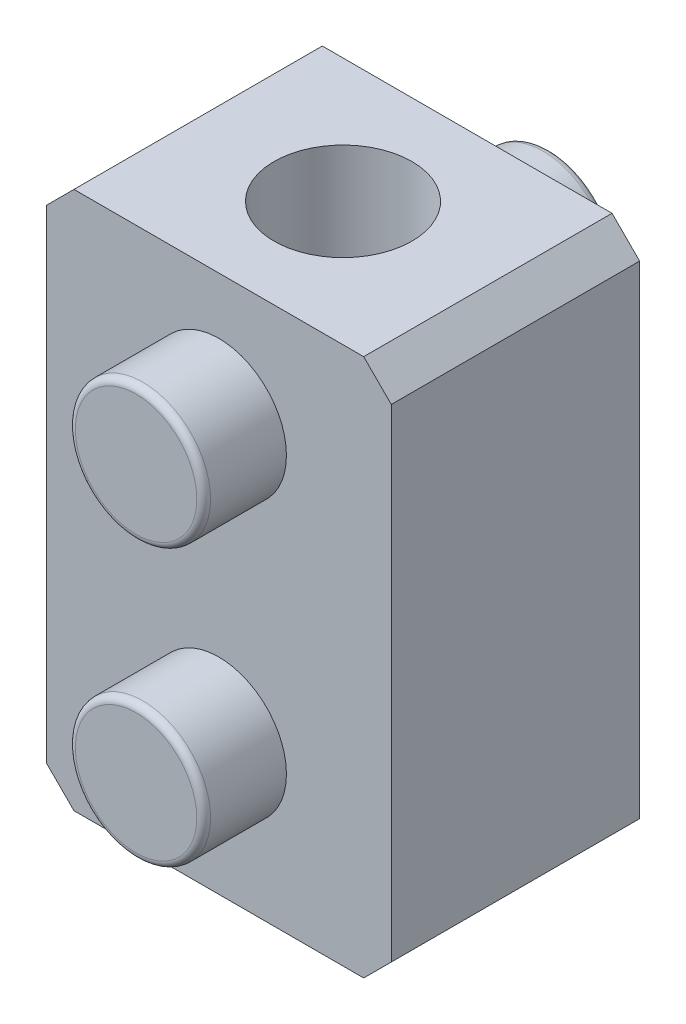
SolidWorks part; units mm, degrees
ref_plane "정면" through (0, 0, 0) normal (0, 0, 1) x (1, 0, 0)
ref_plane "윗면" through (0, 0, 0) normal (0, 1, 0) x (1, 0, 0)
ref_plane "우측면" through (0, 0, 0) normal (1, 0, 0) x (0, 0, -1)
sketch "스케치1" plane through (0, 0, 0) normal (0, 0, 1) x (1, 0, 0)
  line L1 (-6.25, 9.75) -> (6.25, 9.75)
  line L2 (-6.25, 9.75) -> (-6.25, -9.75)
  line L3 (-6.25, -9.75) -> (6.25, -9.75)
  line L4 (6.25, 9.75) -> (6.25, -9.75)
  line L5 (-6.25, 9.75) -> (6.25, -9.75) construction
  line L6 (-6.25, -9.75) -> (6.25, 9.75) construction
  point P0 (0, 0)
  dimension "D1" = 12.5
  dimension "D2" = 19.5
extrude "보스-돌출1" add sketch "스케치1" along normal blind 9
sketch "스케치2" plane through (0, 0, 9) normal (0, 0, 1) x (1, 0, 0)
  line L0 (0, 9.75) -> (0, -9.75) construction
  line L1 (6.25, 9.75) -> (-6.25, 9.75) construction
  line L2 (-6.25, -9.75) -> (6.25, -9.75) construction
  circle A0 centre (0, 5.25) radius 2.45
  circle A1 centre (0, -4.75) radius 2.45
  dimension "D1" = 4.9
  dimension "D2" = 4.9
  dimension "D3" = 10
  dimension "D4" = 5
extrude "보스-돌출2" add sketch "스케치2" along normal blind 3 contours A1 | A0
sketch "스케치4" plane through (0, 0, 0) normal (0, 0, -1) x (-1, 0, 0)
  line L4 (-6.25, 9.75) -> (-6.25, -9.75)
  line L5 (-6.25, -9.75) -> (6.25, -9.75)
  line L6 (6.25, -9.75) -> (6.25, 9.75)
  line L7 (6.25, 9.75) -> (-6.25, 9.75)
  line L8 (-6.25, 9.75) -> (-6.25, -9.75)
  line L9 (-6.25, -9.75) -> (6.25, -9.75)
  line L10 (6.25, -9.75) -> (6.25, 9.75)
  line L11 (6.25, 9.75) -> (-6.25, 9.75)
  circle A0 centre (0, -4.75) radius 2.45 construction
  circle A1 centre (0, -4.75) radius 2.45
  circle A2 centre (0, 5.25) radius 2.45 construction
  circle A3 centre (0, 5.25) radius 2.45
  dimension "D2" = 4.9
  dimension "D3" = 4.9
  dimension "D1" = 0
extrude "보스-돌출3" add sketch "스케치4" along normal blind 3 contours A1 | A3
fillet "필렛1" radius 0.25 4 edges at (2.45, 5.25, 12) (2.45, -4.75, 12) (-2.45, -4.75, -3) (-2.45, 5.25, -3)
sketch "스케치5" plane through (0, -9.75, 0) normal (0, -1, 0) x (1, 0, 0)
  line L0 (6.25, 0) -> (-6.25, 9) construction
  point P4 (0, 4.5)
hole_wizard "M6 탭을 위한 탭 드릴1" positions "3D스케치1" profile "스케치6" hole size "M6" standard "KS" end condition up to next
sketch3d "3D스케치1"
  point P0 (0, -9.75, 4.5)
sketch "스케치6" plane through (0, -9.75, 4.5) normal (1, 0, 0) x (0, 0, -1)
  line L0 (0, 0) -> (0, 19.5)
  line L1 (0, 19.5) -> (2.5, 19.5)
  line L2 (2.5, 19.5) -> (2.5, 0)
  line L5 (2.5, 0) -> (0, 0)
  line L11 (0, -6.35) -> (0, 107.95) construction
  dimension "관통 구멍 지름" = 5
  dimension "관통 구멍 깊이" = 19.5
chamfer "모따기1" distance 1 angle 45 4 edges at (-6.25, 9.75, 4.5) (6.25, 9.75, 4.5) (-6.25, -9.75, 4.5) (6.25, -9.75, 4.5)
